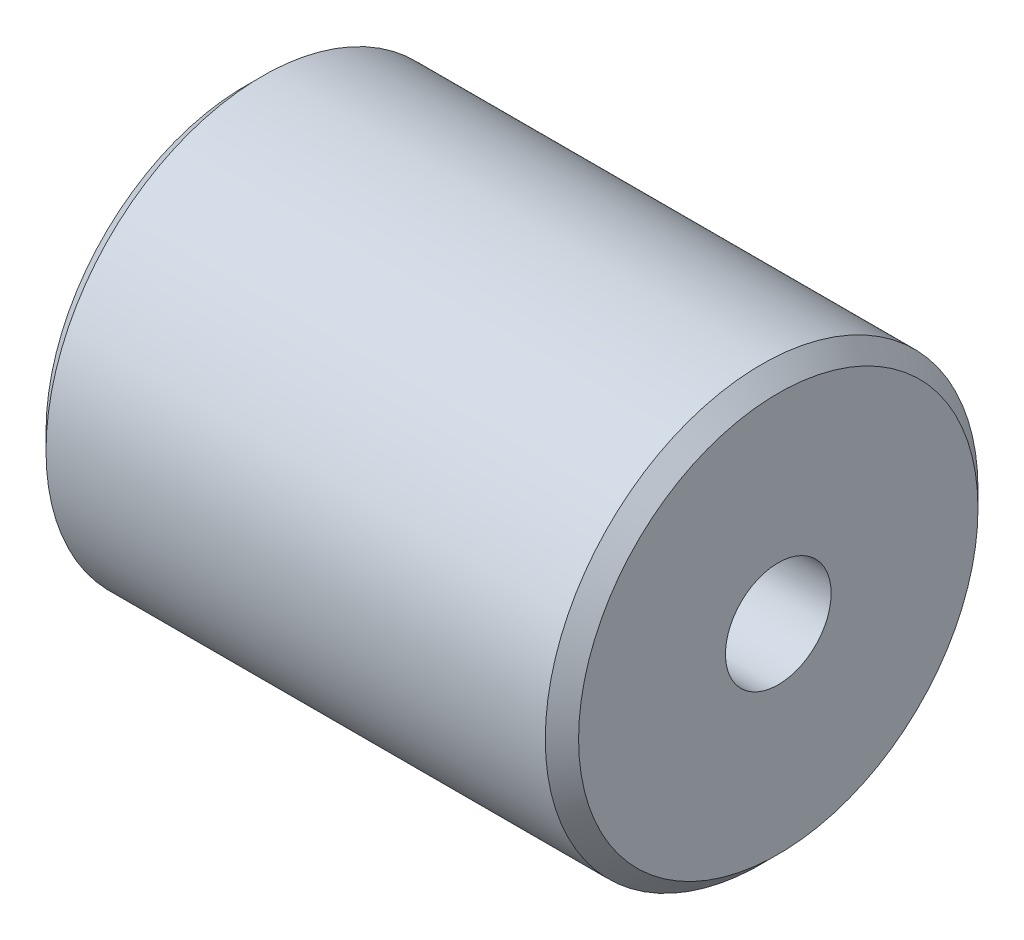
SolidWorks part; units mm, degrees
material "Alumina"
ref_plane "Front Plane" through (0, 0, 0) normal (0, 0, 1) x (1, 0, 0)
ref_plane "Top Plane" through (0, 0, 0) normal (0, 1, 0) x (1, 0, 0)
ref_plane "Right Plane" through (0, 0, 0) normal (1, 0, 0) x (0, 0, -1)
sketch "Sketch1" plane through (0, 0, 0) normal (1, 0, 0) x (0, 0, -1)
  circle A0 centre (0, 0) radius 13
  dimension "D1" = 26
extrude "Boss-Extrude1" add sketch "Sketch1" along normal blind 32
sketch "Sketch2" plane through (32, 0, 0) normal (1, 0, 0) x (0, 0, -1)
  circle A0 centre (0, 0) radius 3.175
  dimension "D1" = 6.35
extrude "Cut-Extrude1" cut sketch "Sketch2" against normal through all
sketch "Sketch3" plane through (0, 0, 0) normal (-1, 0, 0) x (0, 0, 1)
  circle A0 centre (0, 0) radius 5
  dimension "D1" = 10
extrude "Cut-Extrude2" cut sketch "Sketch3" against normal blind 20
chamfer "Chamfer1" distance 1 angle 45 2 edges at (32, 0, -13) (0, 0, -13)
